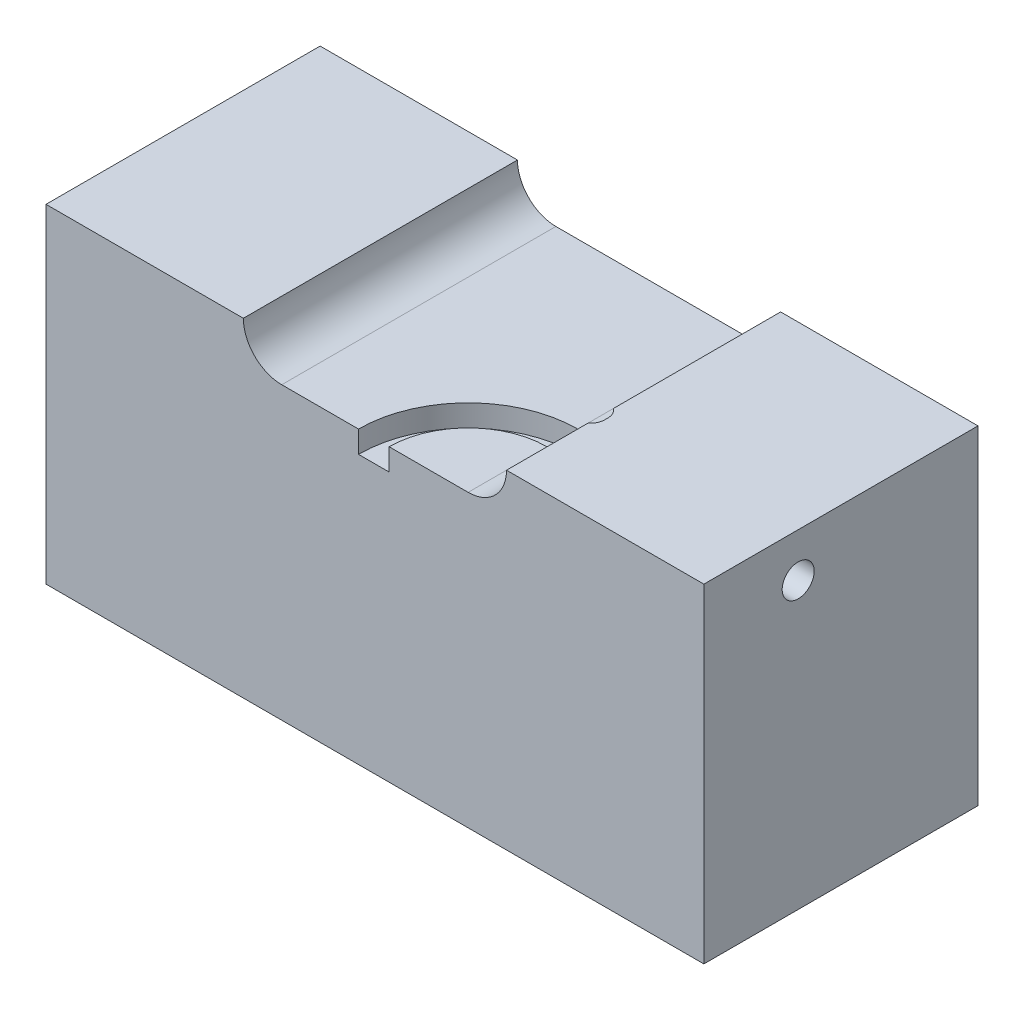
SolidWorks part; units mm, degrees
ref_plane "Front Plane" through (0, 0, 0) normal (0, 0, 1) x (1, 0, 0)
ref_plane "Top Plane" through (0, 0, 0) normal (0, 1, 0) x (1, 0, 0)
ref_plane "Right Plane" through (0, 0, 0) normal (1, 0, 0) x (0, 0, -1)
sketch "Sketch1" plane through (0, 0, 0) normal (0, 1, 0) x (1, 0, 0)
  line L1 (-19.05, -7.9375) -> (19.05, -7.9375)
  line L2 (-19.05, -7.9375) -> (-19.05, 7.9375)
  line L3 (-19.05, 7.9375) -> (19.05, 7.9375)
  line L4 (19.05, -7.9375) -> (19.05, 7.9375)
  line L5 (-19.05, -7.9375) -> (19.05, 7.9375) construction
  line L6 (-19.05, 7.9375) -> (19.05, -7.9375) construction
  point P0 (0, 0)
  dimension "D1" = 38.1
  dimension "D2" = 15.875
extrude "Boss-Extrude1" add sketch "Sketch1" along normal blind 19.05
sketch "Sketch2" plane through (0, 0, -7.9375) normal (0, 0, -1) x (-1, 0, 0)
  line L0 (5.3975, 19.05) -> (-5.3975, 19.05) construction
  line L1 (5.3975, 16.8275) -> (-5.3975, 16.8275)
  line L2 (5.3975, 21.2725) -> (-5.3975, 21.2725)
  line L3 (19.05, 19.05) -> (-19.05, 19.05) construction
  line L4 (-19.05, 0) -> (19.05, 0) construction
  line L6 (19.05, 19.05) -> (19.05, 0) construction
  line L7 (-19.05, 19.05) -> (-19.05, 0) construction
  arc A0 (5.3975, 16.8275) -> (5.3975, 21.2725) centre (5.3975, 19.05) ccw
  arc A1 (-5.3975, 21.2725) -> (-5.3975, 16.8275) centre (-5.3975, 19.05) ccw
  point P2 (0, 19.05)
  dimension "D1" = 19.05
  dimension "D2" = 10.795
  dimension "D3" = 4.445
extrude "Cut-Extrude1" cut sketch "Sketch2" against normal blind 25.4
ref_plane "Plane1" through (0, 16.8275, 0) normal (0, 1, 0) x (1, 0, 0)
sketch "Sketch4" plane through (0, 16.8275, 0) normal (0, 1, 0) x (1, 0, 0)
  line L0 (0, -9.1985) -> (0, 12.0201) construction
  line L1 (0.8255, -7.9375) -> (-0.9525, -7.9375)
  line L2 (5.3975, -3.3655) -> (7.1437, -3.3655)
  line L3 (7.9375, -2.5717) -> (7.9375, -2.3813)
  line L4 (7.1437, -1.5875) -> (5.3975, -1.5875)
  arc A0 (5.3975, -1.5875) -> (-0.9525, -7.9375) centre (5.3975, -7.9375) ccw
  arc A1 (5.3975, -3.3655) -> (0.8255, -7.9375) centre (5.3975, -7.9375) ccw
  arc A2 (7.9375, -2.5717) -> (7.1437, -3.3655) centre (7.1437, -2.5717) cw
  arc A3 (7.9375, -2.3813) -> (7.1437, -1.5875) centre (7.1437, -2.3812) ccw
  dimension "D1" = 12.7
  dimension "D2" = 9.144
  dimension "D3" = 2.54
  dimension "D4" = 0.7937
extrude "Cut-Extrude2" cut sketch "Sketch4" along normal through all and the other way blind 1.27
ref_plane "Plane3" through (19.05, 0, 0) normal (1, 0, 0) x (0, 0, -1)
sketch "Sketch5" plane through (19.05, 0, 0) normal (1, 0, 0) x (0, 0, -1)
  line L0 (-7.9375, 19.05) -> (-7.9375, 0) construction
  line L1 (-7.9375, 19.05) -> (7.9375, 19.05) construction
  circle A0 centre (-2.4765, 16.51) radius 0.9271
  dimension "D2" = 1.8542
  dimension "D1" = 5.461
  dimension "D3" = 2.54
extrude "Cut-Extrude3" cut sketch "Sketch5" against normal blind 12.7
